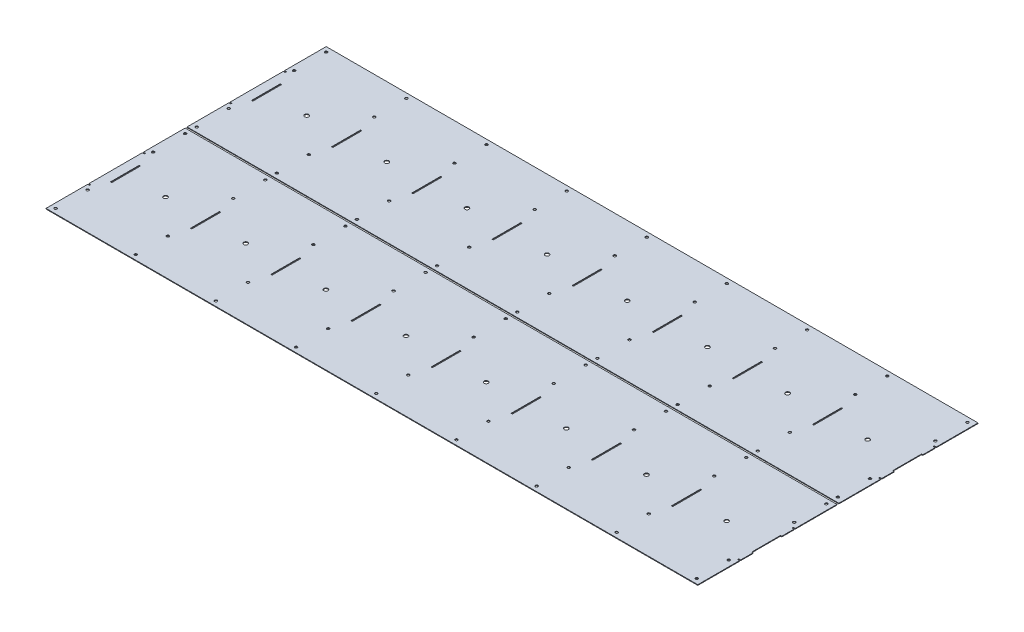
SolidWorks part; units mm, degrees
ref_plane "Front Plane" through (0, 0, 0) normal (0, 0, 1) x (1, 0, 0)
ref_plane "Top Plane" through (0, 0, 0) normal (0, 1, 0) x (1, 0, 0)
ref_plane "Right Plane" through (0, 0, 0) normal (1, 0, 0) x (0, 0, -1)
sketch "Sketch1" plane through (0, 0, 0) normal (0, 1, 0) x (1, 0, 0)
  line L0 (-8, 41.5) -> (-8, -41.5) construction
  line L1 (-8, 0) -> (0, 0) construction
  line L2 (-8, -41.5) -> (-8, -43.5) construction
  line L3 (-8, -43.5) -> (-8, -51) construction
  line L4 (-8, -51) -> (-8, -101) construction
  line L5 (0, 0) -> (125, 0) construction
  line L6 (-8, 41.5) -> (-8, 43.5) construction
  line L7 (-8, 43.5) -> (-8, 51) construction
  line L8 (-8, 51) -> (-8, 101) construction
  line L9 (117, -51) -> (117, -101) construction
  line L10 (117, -43.5) -> (117, -51) construction
  line L11 (117, -41.5) -> (117, -43.5) construction
  line L12 (117, 41.5) -> (117, -41.5) construction
  line L13 (117, 0) -> (125, 0) construction
  line L14 (124, -22.5) -> (126, -22.5)
  line L15 (-1, 22.5) -> (1, 22.5)
  line L16 (-1, 22.5) -> (-1, -22.5)
  line L17 (-1, -22.5) -> (1, -22.5)
  line L18 (1, 22.5) -> (1, -22.5)
  line L19 (-1, 22.5) -> (1, -22.5) construction
  line L20 (-1, -22.5) -> (1, 22.5) construction
  line L21 (124, 22.5) -> (124, -22.5)
  line L22 (124, -22.5) -> (126, 22.5) construction
  line L23 (124, 22.5) -> (126, -22.5) construction
  line L24 (126, 22.5) -> (126, -22.5)
  line L25 (124, 22.5) -> (126, 22.5)
  line L26 (117, 41.5) -> (117, 43.5) construction
  line L27 (117, 43.5) -> (117, 51) construction
  line L28 (117, 51) -> (117, 101) construction
  line L29 (242, -51) -> (242, -101) construction
  line L30 (242, -43.5) -> (242, -51) construction
  line L31 (242, -41.5) -> (242, -43.5) construction
  line L32 (242, 41.5) -> (242, -41.5) construction
  line L33 (242, 0) -> (250, 0) construction
  line L34 (249, -22.5) -> (251, -22.5)
  line L35 (249, 22.5) -> (249, -22.5)
  line L36 (249, -22.5) -> (251, 22.5) construction
  line L37 (249, 22.5) -> (251, -22.5) construction
  line L38 (251, 22.5) -> (251, -22.5)
  line L39 (249, 22.5) -> (251, 22.5)
  line L40 (242, 41.5) -> (242, 43.5) construction
  line L41 (242, 43.5) -> (242, 51) construction
  line L42 (242, 51) -> (242, 101) construction
  line L43 (367, -51) -> (367, -101) construction
  line L44 (367, -43.5) -> (367, -51) construction
  line L45 (367, -41.5) -> (367, -43.5) construction
  line L46 (367, 41.5) -> (367, -41.5) construction
  line L47 (367, 0) -> (375, 0) construction
  line L48 (374, -22.5) -> (376, -22.5)
  line L49 (374, 22.5) -> (374, -22.5)
  line L50 (374, -22.5) -> (376, 22.5) construction
  line L51 (374, 22.5) -> (376, -22.5) construction
  line L52 (376, 22.5) -> (376, -22.5)
  line L53 (374, 22.5) -> (376, 22.5)
  line L54 (367, 41.5) -> (367, 43.5) construction
  line L55 (367, 43.5) -> (367, 51) construction
  line L56 (367, 51) -> (367, 101) construction
  line L57 (-15.5, -108.5) -> (1001, -108.5)
  line L58 (1001, -108.5) -> (1001, -43.5)
  line L59 (1001, -43.5) -> (998, -43.5)
  line L60 (998, -43.5) -> (998, -41.5)
  line L61 (998, -41.5) -> (1001, -41.5)
  line L62 (1001, -41.5) -> (1001, -22.5)
  line L63 (1001, 41.5) -> (998, 41.5)
  line L64 (998, 41.5) -> (998, 43.5)
  line L65 (998, 43.5) -> (1001, 43.5)
  line L66 (1001, 43.5) -> (1001, 108.5)
  line L67 (1001, 108.5) -> (-15.5, 108.5)
  line L68 (-15.5, 108.5) -> (-15.5, 43.5)
  line L69 (-15.5, 43.5) -> (-12.5, 43.5)
  line L70 (-12.5, 43.5) -> (-12.5, 41.5)
  line L71 (-12.5, 41.5) -> (-15.5, 41.5)
  line L72 (-15.5, 41.5) -> (-15.5, -41.5)
  line L73 (-15.5, -41.5) -> (-12.5, -41.5)
  line L74 (-12.5, -41.5) -> (-12.5, -43.5)
  line L75 (-12.5, -43.5) -> (-15.5, -43.5)
  line L76 (-15.5, -43.5) -> (-15.5, -108.5)
  line L77 (992, -51) -> (992, -101) construction
  line L78 (-15.5, 0) -> (-8, 0) construction
  line L79 (-12.5, -41.5) -> (-8, -41.5) construction
  line L80 (998, 43.5) -> (-12.5, 43.5) construction
  line L81 (-12.5, 41.5) -> (998, 41.5) construction
  line L82 (998, -41.5) -> (-12.5, -41.5) construction
  line L83 (-12.5, -43.5) -> (998, -43.5) construction
  line L84 (492, -51) -> (492, -101) construction
  line L85 (492, -43.5) -> (492, -51) construction
  line L86 (492, -41.5) -> (492, -43.5) construction
  line L87 (492, 41.5) -> (492, -41.5) construction
  line L88 (492, 0) -> (500, 0) construction
  line L89 (499, -22.5) -> (501, -22.5)
  line L90 (499, 22.5) -> (499, -22.5)
  line L91 (499, -22.5) -> (501, 22.5) construction
  line L92 (499, 22.5) -> (501, -22.5) construction
  line L93 (501, 22.5) -> (501, -22.5)
  line L94 (499, 22.5) -> (501, 22.5)
  line L95 (492, 41.5) -> (492, 43.5) construction
  line L96 (492, 43.5) -> (492, 51) construction
  line L97 (492, 51) -> (492, 101) construction
  line L98 (617, -51) -> (617, -101) construction
  line L99 (617, -43.5) -> (617, -51) construction
  line L100 (617, -41.5) -> (617, -43.5) construction
  line L101 (617, 41.5) -> (617, -41.5) construction
  line L102 (617, 0) -> (625, 0) construction
  line L103 (624, -22.5) -> (626, -22.5)
  line L104 (624, 22.5) -> (624, -22.5)
  line L105 (624, -22.5) -> (626, 22.5) construction
  line L106 (624, 22.5) -> (626, -22.5) construction
  line L107 (626, 22.5) -> (626, -22.5)
  line L108 (624, 22.5) -> (626, 22.5)
  line L109 (617, 41.5) -> (617, 43.5) construction
  line L110 (617, 43.5) -> (617, 51) construction
  line L111 (617, 51) -> (617, 101) construction
  line L112 (742, -51) -> (742, -101) construction
  line L113 (742, -43.5) -> (742, -51) construction
  line L114 (742, -41.5) -> (742, -43.5) construction
  line L115 (742, 41.5) -> (742, -41.5) construction
  line L116 (742, 0) -> (750, 0) construction
  line L117 (749, -22.5) -> (751, -22.5)
  line L118 (749, 22.5) -> (749, -22.5)
  line L119 (749, -22.5) -> (751, 22.5) construction
  line L120 (749, 22.5) -> (751, -22.5) construction
  line L121 (751, 22.5) -> (751, -22.5)
  line L122 (749, 22.5) -> (751, 22.5)
  line L123 (742, 41.5) -> (742, 43.5) construction
  line L124 (742, 43.5) -> (742, 51) construction
  line L125 (742, 51) -> (742, 101) construction
  line L126 (867, -51) -> (867, -101) construction
  line L127 (867, -43.5) -> (867, -51) construction
  line L128 (867, -41.5) -> (867, -43.5) construction
  line L129 (867, 41.5) -> (867, -41.5) construction
  line L130 (867, 0) -> (875, 0) construction
  line L131 (874, -22.5) -> (876, -22.5)
  line L132 (874, 22.5) -> (874, -22.5)
  line L133 (874, -22.5) -> (876, 22.5) construction
  line L134 (874, 22.5) -> (876, -22.5) construction
  line L135 (876, 22.5) -> (876, -22.5)
  line L136 (874, 22.5) -> (876, 22.5)
  line L137 (867, 41.5) -> (867, 43.5) construction
  line L138 (867, 43.5) -> (867, 51) construction
  line L139 (867, 51) -> (867, 101) construction
  line L140 (992, -43.5) -> (992, -51) construction
  line L141 (992, -41.5) -> (992, -43.5) construction
  line L142 (992, 41.5) -> (992, -41.5) construction
  line L143 (992, 0) -> (1000, 0) construction
  line L144 (999, -22.5) -> (1001, -22.5)
  line L145 (999, 22.5) -> (999, -22.5)
  line L146 (999, -22.5) -> (1001, 22.5) construction
  line L147 (999, 22.5) -> (1001, -22.5) construction
  line L149 (999, 22.5) -> (1001, 22.5)
  line L150 (992, 41.5) -> (992, 43.5) construction
  line L151 (992, 43.5) -> (992, 51) construction
  line L152 (992, 51) -> (992, 101) construction
  line L153 (1001, 22.5) -> (1001, 41.5)
  line L154 (1001, 22.5) -> (1001, -22.5) construction
  line L155 (1001, 22.5) -> (1001, -22.5) construction
  circle A0 centre (-8, -101) radius 2
  circle A1 centre (-8, -51) radius 2
  circle A2 centre (-8, 51) radius 2
  circle A3 centre (-8, 101) radius 2
  circle A4 centre (117, -101) radius 2
  circle A5 centre (117, -51) radius 2
  circle A6 centre (117, 51) radius 2
  circle A7 centre (117, 101) radius 2
  circle A8 centre (242, -101) radius 2
  circle A9 centre (242, -51) radius 2
  circle A10 centre (242, 51) radius 2
  circle A11 centre (242, 101) radius 2
  circle A12 centre (367, -101) radius 2
  circle A13 centre (367, -51) radius 2
  circle A14 centre (367, 51) radius 2
  circle A15 centre (367, 101) radius 2
  circle A16 centre (62.5, 0) radius 3.175
  circle A17 centre (187.5, 0) radius 3.175
  circle A18 centre (312.5, 0) radius 3.175
  circle A19 centre (437.5, 0) radius 3.175
  circle A20 centre (492, -101) radius 2
  circle A21 centre (492, -51) radius 2
  circle A22 centre (492, 51) radius 2
  circle A23 centre (492, 101) radius 2
  circle A24 centre (562.5, 0) radius 3.175
  circle A25 centre (617, -101) radius 2
  circle A26 centre (617, -51) radius 2
  circle A27 centre (617, 51) radius 2
  circle A28 centre (617, 101) radius 2
  circle A29 centre (687.5, 0) radius 3.175
  circle A30 centre (742, -101) radius 2
  circle A31 centre (742, -51) radius 2
  circle A32 centre (742, 51) radius 2
  circle A33 centre (742, 101) radius 2
  circle A34 centre (812.5, 0) radius 3.175
  circle A35 centre (867, -101) radius 2
  circle A36 centre (867, -51) radius 2
  circle A37 centre (867, 51) radius 2
  circle A38 centre (867, 101) radius 2
  circle A39 centre (937.5, 0) radius 3.175
  circle A40 centre (992, -101) radius 2
  circle A41 centre (992, -51) radius 2
  circle A42 centre (992, 51) radius 2
  circle A43 centre (992, 101) radius 2
  circle A44 centre (1062.5, 0) radius 3.175 construction
  point P14 (0, 0)
  dimension "D1" = 83
  dimension "D2" = 4
  dimension "D18" = 6.35
  dimension "D19" = 6.35
  dimension "D3" = 8
  dimension "D4" = 45
  dimension "D5" = 2
  dimension "D6" = 50
  dimension "D7" = 2
  dimension "D8" = 7.5
  dimension "D9" = 125
  dimension "D11" = 125
  dimension "D12" = 7.5
  dimension "D13" = 3
  dimension "D15" = 3
  dimension "D16" = 7.5
  dimension "D17" = 7.5
  dimension "D10" = 9
extrude "Boss-Extrude1" add sketch "Sketch1" along normal blind 1
pattern_linear "LPattern1" count 2 spacing 220 along (0, 0, -1) of bodies 101
